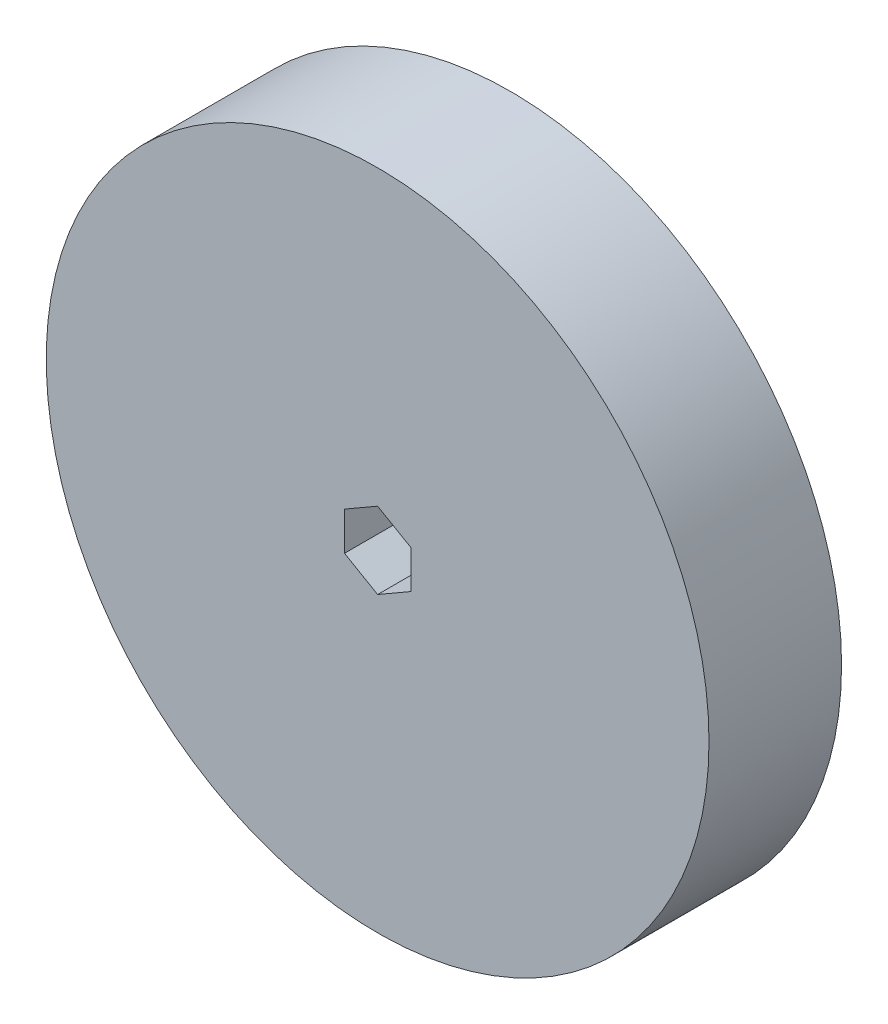
SolidWorks part; units mm, degrees
ref_plane "Front Plane" through (0, 0, 0) normal (0, 0, 1) x (1, 0, 0)
ref_plane "Top Plane" through (0, 0, 0) normal (0, 1, 0) x (1, 0, 0)
ref_plane "Right Plane" through (0, 0, 0) normal (1, 0, 0) x (0, 0, -1)
sketch "Sketch1" plane through (0, 0, 0) normal (0, 0, 1) x (1, 0, 0)
  line L1 (0, 7.3323) -> (-6.35, 3.6662)
  line L2 (-6.35, 3.6662) -> (-6.35, -3.6662)
  line L3 (-6.35, -3.6662) -> (0, -7.3323)
  line L4 (0, -7.3323) -> (6.35, -3.6662)
  line L5 (6.35, -3.6662) -> (6.35, 3.6662)
  line L6 (6.35, 3.6662) -> (0, 7.3323)
  circle A0 centre (0, 0) radius 63.5
  circle A1 centre (0, 0) radius 6.35 construction
  dimension "D1" = 127
  dimension "D2" = 12.7
extrude "Boss-Extrude1" add sketch "Sketch1" along normal blind 25.4
